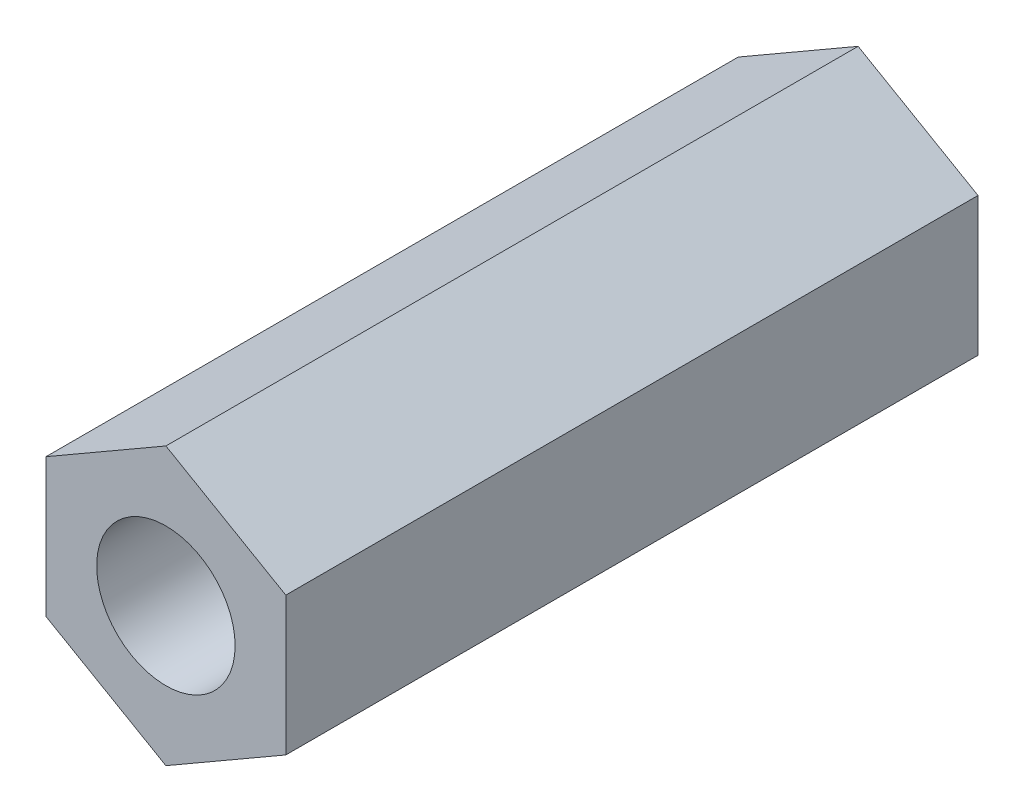
SolidWorks part; units mm, degrees
ref_plane "Front Plane" through (0, 0, 0) normal (0, 0, 1) x (1, 0, 0)
ref_plane "Top Plane" through (0, 0, 0) normal (0, 1, 0) x (1, 0, 0)
ref_plane "Right Plane" through (0, 0, 0) normal (1, 0, 0) x (0, 0, -1)
sketch "Sketch1" plane through (0, 0, 0) normal (0, 0, 1) x (1, 0, 0)
  line L1 (0, 0.5) -> (-0.433, 0.25)
  line L2 (-0.433, 0.25) -> (-0.433, -0.25)
  line L3 (-0.433, -0.25) -> (0, -0.5)
  line L4 (0, -0.5) -> (0.433, -0.25)
  line L5 (0.433, -0.25) -> (0.433, 0.25)
  line L6 (0.433, 0.25) -> (0, 0.5)
  circle A0 centre (0, 0) radius 0.433 construction
  circle A1 centre (0, 0) radius 0.25
  dimension "D2" = 0.5
  dimension "D1" = 1
extrude "Boss-Extrude1" add sketch "Sketch1" along normal blind 2.5
